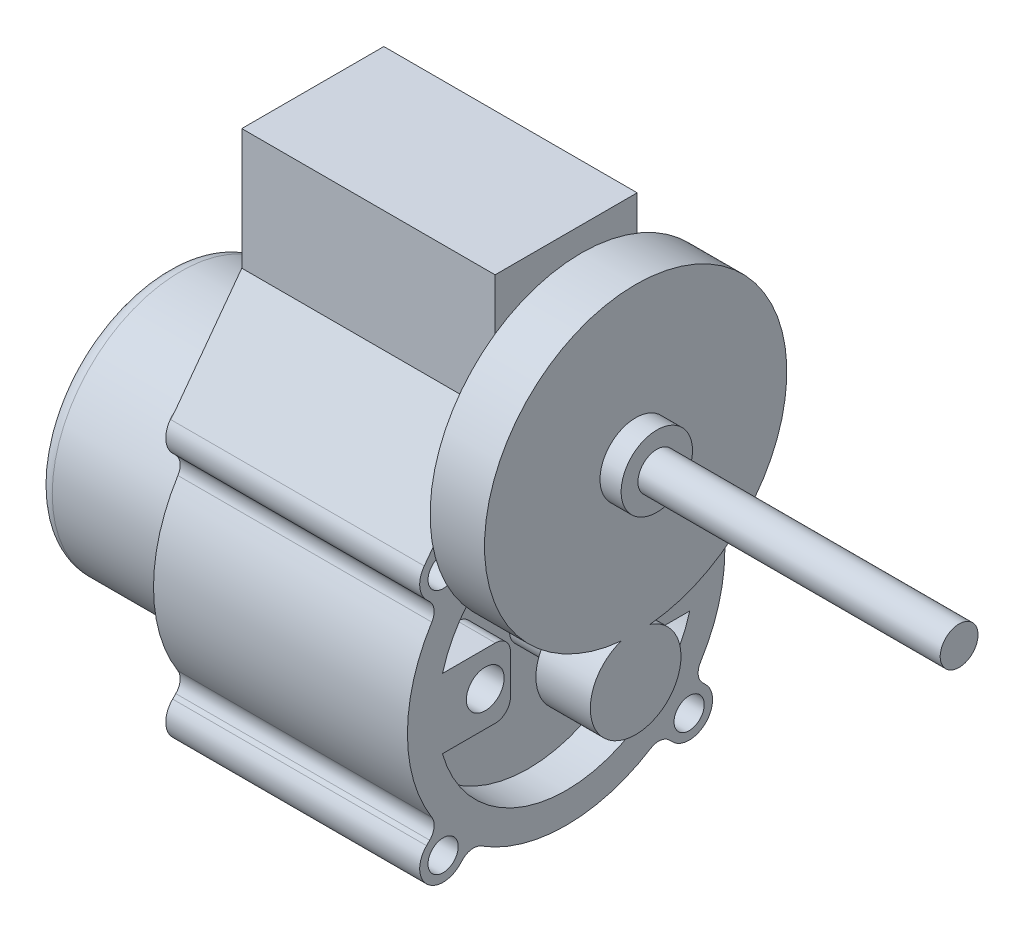
SolidWorks part; units mm, degrees
ref_plane "Front Plane" through (0, 0, 0) normal (0, 0, 1) x (1, 0, 0)
ref_plane "Top Plane" through (0, 0, 0) normal (0, 1, 0) x (1, 0, 0)
ref_plane "Right Plane" through (0, 0, 0) normal (1, 0, 0) x (0, 0, -1)
sketch "Sketch1" plane through (0, 0, 0) normal (1, 0, 0) x (0, 0, -1)
  line L0 (0, 0) -> (0, 13.335) construction
  circle A0 centre (0, 0) radius 10.795
  circle A1 centre (0, 0) radius 13.335
  dimension "D1" = 26.67
  dimension "D2" = 2.54
extrude "Boss-Extrude1" add sketch "Sketch1" against normal blind 21.336
sketch "Sketch2" plane through (0, 0, 0) normal (1, 0, 0) x (0, 0, -1)
  line L0 (0, 0) -> (10.3363, -10.3363) construction
  line L1 (8.9443, -11.7282) -> (7.934, -10.7179)
  line L2 (11.7282, -8.9443) -> (10.7179, -7.934)
  line L3 (0, 0) -> (0, -10.795) construction
  arc A0 (11.7282, -8.9443) -> (8.9443, -11.7282) centre (10.3363, -10.3363) cw
  circle A1 centre (0, 0) radius 13.335 construction
  circle A2 centre (10.3363, -10.3363) radius 1.27
  arc A3 (10.7179, -7.934) -> (7.934, -10.7179) centre (0, 0) cw
  circle A4 centre (0, 0) radius 10.795 construction
  point P10 (11.7282, -11.7282)
  point P11 (9.4293, -9.4293)
  dimension "D2" = 2.54
  dimension "D1" = 3.937
  dimension "D3" = 3.2512
  dimension "D4" = 45
extrude "Boss-Extrude2" add sketch "Sketch2" against normal blind 21.336
fillet "Fillet1" radius 1.27 2 edges at (-10.668, -10.7179, -7.934) (-10.668, -7.934, -10.7179)
pattern_circular "CirPattern1" count 4 over 360 about axis through (0, 0, 0) along (1, 0, 0) of "Boss-Extrude2", "Fillet1"
sketch "Sketch3" plane through (0, 0, 0) normal (1, 0, 0) x (0, 0, -1)
  line L0 (10.795, 0) -> (-10.795, 0) construction
  line L1 (0, 0) -> (0, 10.795) construction
  line L2 (-10.3923, 2.921) -> (-4.6773, 2.921)
  line L3 (-4.6773, 2.921) -> (-4.6773, -2.921)
  line L4 (-4.6773, -2.921) -> (-10.3923, -2.921)
  line L5 (10.3923, 2.921) -> (4.6773, 2.921)
  line L6 (4.6773, 2.921) -> (4.6773, -2.921)
  line L7 (4.6773, -2.921) -> (10.3923, -2.921)
  circle A0 centre (0, 0) radius 10.795 construction
  circle A1 centre (-6.7945, 0) radius 1.5875
  circle A2 centre (6.7945, 0) radius 1.5875
  arc A4 (-10.3923, 2.921) -> (-10.3923, -2.921) centre (0, 0) ccw
  arc A5 (10.3923, -2.921) -> (10.3923, 2.921) centre (0, 0) ccw
  dimension "D3" = 3.175
  dimension "D1" = 5.842
  dimension "D2" = 5.715
  dimension "D4" = 13.589
  dimension "D5" = 5.715
extrude "Boss-Extrude3" add sketch "Sketch3" against normal blind 3.175
fillet "Fillet2" radius 1.27 4 edges at (-1.5875, -2.921, -4.6773) (-1.5875, 2.921, -4.6773) (-1.5875, -2.921, 4.6773) (-1.5875, 2.921, 4.6773)
sketch "Sketch4" plane through (-3.175, 0, 0) normal (-1, 0, 0) x (0, 0, 1)
  circle A0 centre (0, 0) radius 10.795 construction
  circle A1 centre (0, 0) radius 10.795
extrude "Boss-Extrude4" add sketch "Sketch4" along normal blind 30.48
fillet "Fillet3" radius 1.27 1 edges at (-33.655, 0, 10.795)
sketch "Sketch5" plane through (0, 0, 0) normal (1, 0, 0) x (0, 0, -1)
  line L0 (-11.9194, 11.5062) -> (-5.969, 19.558)
  line L1 (0, 0) -> (0, 29.718) construction
  line L2 (-5.969, 19.558) -> (-5.969, 29.718)
  line L3 (-5.969, 29.718) -> (5.969, 29.718)
  line L4 (5.969, 29.718) -> (5.969, 19.558)
  line L5 (5.969, 19.558) -> (11.9194, 11.5062)
  line L6 (8.9443, 11.7282) -> (8.6783, 11.4621) construction
  line L7 (8.9443, 11.7282) -> (8.6783, 11.4621)
  line L8 (-8.6783, 11.4621) -> (-8.9443, 11.7282) construction
  line L9 (-8.6783, 11.4621) -> (-8.9443, 11.7282)
  arc A0 (-8.9443, 11.7282) -> (-11.7282, 8.9443) centre (-10.3363, 10.3363) ccw construction
  arc A1 (11.7282, 8.9443) -> (8.9443, 11.7282) centre (10.3363, 10.3363) ccw construction
  arc A2 (-8.6783, 11.4621) -> (-7.1037, 11.2854) centre (-7.7802, 12.3602) ccw construction
  arc A3 (7.1037, 11.2854) -> (-7.1037, 11.2854) centre (0, 0) ccw construction
  arc A4 (7.1037, 11.2854) -> (8.6783, 11.4621) centre (7.7802, 12.3602) ccw construction
  arc A5 (-8.9443, 11.7282) -> (-11.9194, 11.5062) centre (-10.3363, 10.3363) ccw
  arc A6 (-8.6783, 11.4621) -> (-7.1037, 11.2854) centre (-7.7802, 12.3602) ccw
  arc A7 (7.1037, 11.2854) -> (-7.1037, 11.2854) centre (0, 0) ccw
  arc A8 (7.1037, 11.2854) -> (8.6783, 11.4621) centre (7.7802, 12.3602) ccw
  arc A9 (11.9194, 11.5062) -> (8.9443, 11.7282) centre (10.3363, 10.3363) ccw
  point P8 (0, 0)
  point P16 (0, 0)
  dimension "D1" = 11.938
  dimension "D2" = 29.718
  dimension "D3" = 10.16
extrude "Boss-Extrude5" add sketch "Sketch5" against normal blind 21.2852
sketch "Sketch6" plane through (-3.175, 0, 0) normal (1, 0, 0) x (0, 0, -1)
  circle A0 centre (0, 0) radius 1.5875
  dimension "D1" = 3.175
extrude "Boss-Extrude6" add sketch "Sketch6" along normal blind 6.985
sketch "Sketch7" plane through (0, 0, 0) normal (1, 0, 0) x (0, 0, -1)
  line L0 (0, 16.256) -> (0, 0.3391) construction
  circle A0 centre (0, 16.256) radius 4.064
  dimension "D1" = 8.128
  dimension "D2" = 16.256
extrude "Boss-Extrude7" add sketch "Sketch7" along normal blind 1.27
sketch "Sketch8" plane through (1.27, 0, 0) normal (1, 0, 0) x (0, 0, -1)
  circle A0 centre (0, 16.256) radius 12.7
  circle A1 centre (0, 0) radius 3.556 construction
  circle A2 centre (0, 0) radius 3.81
  circle M1 centre (0, 16.256) radius 4.064
  dimension "D1" = 25.4
  dimension "D2" = 0.254
extrude "Boss-Extrude10" add sketch "Sketch8" along normal blind 4.572 contours A0 M1 | M1 | A2
sketch "Sketch9" plane through (5.842, 0, 0) normal (1, 0, 0) x (0, 0, -1)
  circle A0 centre (0, 16.256) radius 2.9972
  dimension "D1" = 5.9944
extrude "Boss-Extrude12" add sketch "Sketch9" along normal blind 1.778
sketch "Sketch10" plane through (7.62, 0, 0) normal (1, 0, 0) x (0, 0, -1)
  circle A0 centre (0, 16.256) radius 1.5875
  dimension "D1" = 3.175
extrude "Boss-Extrude13" add sketch "Sketch10" along normal blind 25.4
equation "\"D5@Sketch3\"=\"D2@Sketch3\""
